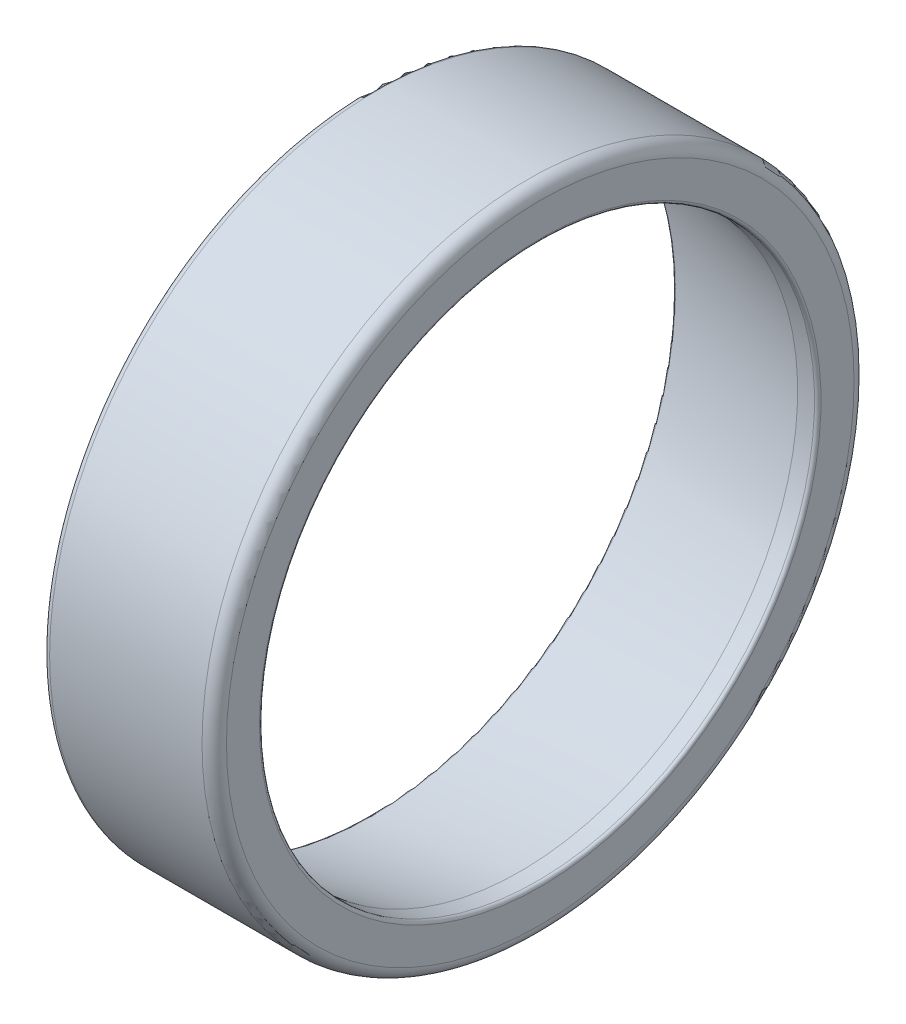
SolidWorks part; units mm, degrees
ref_plane "Front Plane" through (0, 0, 0) normal (0, 0, 1) x (1, 0, 0)
ref_plane "Top Plane" through (0, 0, 0) normal (0, 1, 0) x (1, 0, 0)
ref_plane "Right Plane" through (0, 0, 0) normal (1, 0, 0) x (0, 0, -1)
sketch "Sketch1" plane through (0, 0, 0) normal (0, 0, 1) x (1, 0, 0)
  line L0 (0, 0) -> (21, 0) construction
  line L1 (3.4, 37.5505) -> (3.4, 26.4356) construction
  line L2 (0, 37.5505) -> (3.4, 37.5505) construction
  line L3 (0, 37.5505) -> (0, 27.5) construction
  line L4 (0, 27.5) -> (21, 27.5) construction
  line L5 (21, 25.127) -> (21, 27.5) construction
  line L6 (2.0778, 35.0968) -> (20.2251, 31.8969) construction
  line L7 (22, 34.05) -> (22, 40)
  line L8 (22, 40) -> (1, 40)
  line L9 (1, 37.3177) -> (1, 40)
  line L10 (3.4, 26.4356) -> (18.3572, 25.127) construction
  line L11 (1, 37.3177) -> (19.5319, 34.05)
  line L12 (4.0729, 31.5464) -> (18.9445, 29.5885) construction
  line L13 (3.4, 26.4356) -> (4.7457, 36.6572) construction
  line L14 (18.3572, 25.127) -> (19.5319, 34.05) construction
  line L15 (18.3572, 25.127) -> (21, 25.127) construction
  line L16 (23.2, 28.3516) -> (23.2, 26.127) construction
  line L17 (1.8, 33.5211) -> (19.9473, 30.3212) construction
  line L18 (21.6, 28.3516) -> (21.6, 26.127) construction
  line L19 (21.6, 26.127) -> (23.2, 26.127) construction
  line L20 (1.8, 33.5211) -> (2.0778, 35.0968) construction
  line L21 (19.5319, 34.05) -> (22, 34.05)
  arc A0 (19.9473, 30.3212) -> (21.6, 28.3516) centre (19.6, 28.3516) cw construction
  arc A1 (20.2251, 31.8969) -> (23.2, 28.3516) centre (19.6, 28.3516) cw construction
  dimension "D14" = 2
  dimension "D15" = 3.6
  dimension "D1" = 21
  dimension "D2" = 27.5
  dimension "D3" = 40
  dimension "D4" = 1
  dimension "D5" = 21
  dimension "D6" = 5
  dimension "D7" = 1.8
  dimension "D8" = 2.5
  dimension "D9" = 15
  dimension "D10" = 9
  dimension "D11" = 2
  dimension "D12" = 1.6
  dimension "D13" = 1.6
  dimension "D16" = 0.6
  dimension "D17" = 1
  dimension "D18" = 3.4
  dimension "D19" = 5
  dimension "D20" = 5.95
  dimension "D21" = 31.8969
  dimension "D22" = 40
revolve "Revolve1" add sketch "Sketch1" angle 360 about L0
fillet "Fillet1" radius 1.5 1 edges at (22, 0, 40)
fillet "Fillet2" radius 0.8 1 edges at (1, 0, 40)
fillet "Fillet3" radius 0.4 2 edges at (1, 0, 37.3177) (22, 0, 34.05)
